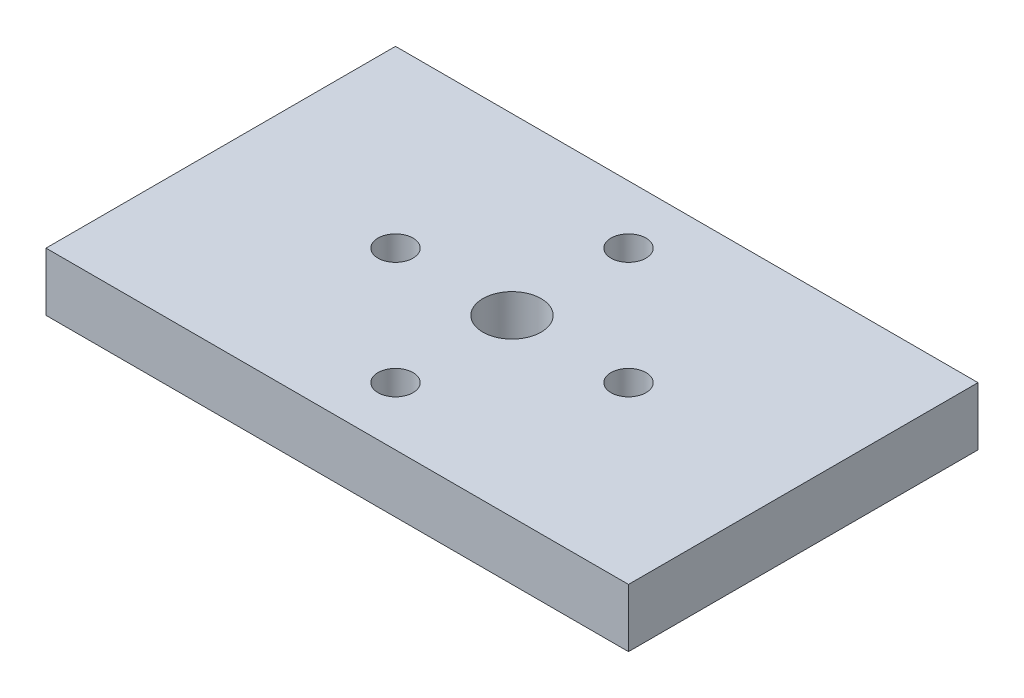
SolidWorks part; units mm, degrees
ref_plane "前视基准面" through (0, 0, 0) normal (0, 0, 1) x (1, 0, 0)
ref_plane "上视基准面" through (0, 0, 0) normal (0, 1, 0) x (1, 0, 0)
ref_plane "右视基准面" through (0, 0, 0) normal (1, 0, 0) x (0, 0, -1)
other "Configuration Table"
sketch "草图1" plane through (0, 0, 0) normal (0, 1, 0) x (1, 0, 0)
  line L1 (-50, -30) -> (50, -30)
  line L2 (-50, -30) -> (-50, 30)
  line L3 (-50, 30) -> (50, 30)
  line L4 (50, -30) -> (50, 30)
  line L5 (0, 30) -> (0, -30) construction
  line L6 (-50, 0) -> (50, 0) construction
  point P0 (0, 0)
extrude "凸台-拉伸1" add sketch "草图1" along normal blind 10
sketch "草图2" plane through (0, 0, 0) normal (0, 1, 0) x (1, 0, 0)
  circle A0 centre (0, 0) radius 5
extrude "切除-拉伸1" cut sketch "草图2" along normal blind 20
sketch "草图3" plane through (0, 0, 0) normal (0, 1, 0) x (1, 0, 0)
  circle A0 centre (20, 0) radius 3
extrude "切除-拉伸2" cut sketch "草图3" along normal blind 20
pattern_circular "阵列(圆周)1" count 4 over 360 about axis through (0, 0, 0) along (0, 1, 0) of "切除-拉伸2"
